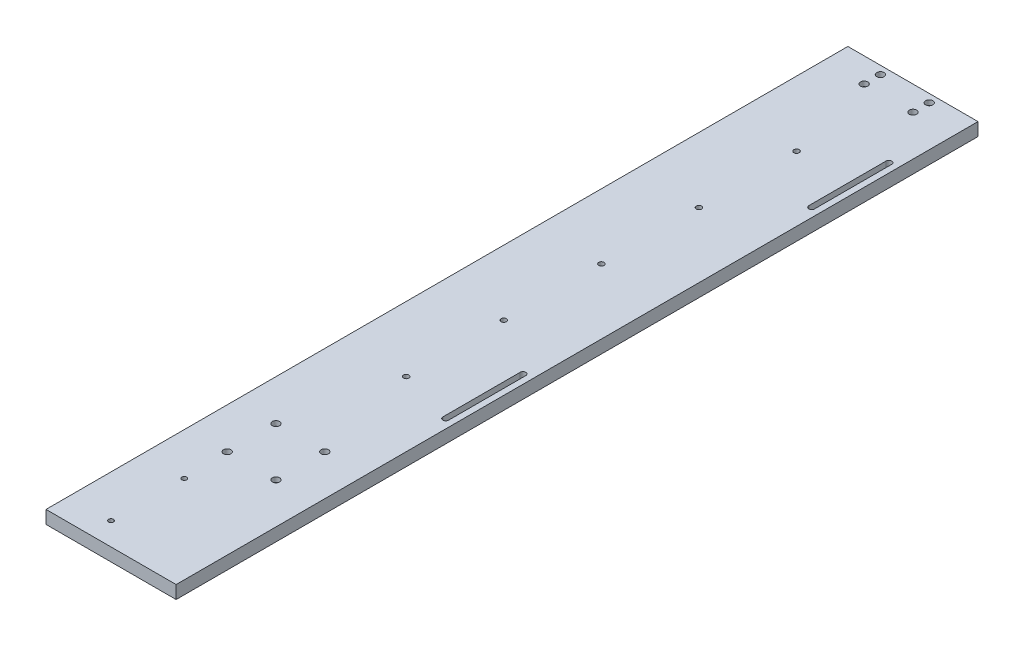
SolidWorks part; units mm, degrees
material "6061 Сплав"
ref_plane "Front" through (0, 0, 0) normal (0, 0, 1) x (1, 0, 0)
ref_plane "Top" through (0, 0, 0) normal (0, 1, 0) x (1, 0, 0)
ref_plane "Right" through (0, 0, 0) normal (1, 0, 0) x (0, 0, -1)
sketch "Эскиз1" plane through (0, 0, 0) normal (0, 0, 1) x (1, 0, 0)
  line L1 (-40, 4) -> (40, 4)
  line L2 (-40, 4) -> (-40, -4)
  line L3 (-40, -4) -> (40, -4)
  line L4 (40, 4) -> (40, -4)
  line L5 (-40, 4) -> (40, -4) construction
  line L6 (-40, -4) -> (40, 4) construction
  point P0 (0, 0)
  dimension "D1" = 80
  dimension "D2" = 8
extrude "Бобышка-Вытянуть1" add sketch "Эскиз1" along normal blind 1000
sketch "Эскиз3" plane through (0, -4, 0) normal (0, -1, 0) x (1, 0, 0)
  line L0 (-40, 1000) -> (-40, 0) construction
  line L1 (-40, 0) -> (40, 0) construction
  circle A0 centre (15, 512) radius 4
  circle A1 centre (-15, 512) radius 4
  dimension "D1" = 30
  dimension "D2" = 25
  dimension "D3" = 512
extrude "Вырез-Вытянуть1" cut sketch "Эскиз3" against normal blind 5
sketch "Эскиз4" plane through (0, 1, 0) normal (0, -1, 0) x (1, 0, 0)
  circle A0 centre (-15, 512) radius 2.25
  circle A1 centre (15, 512) radius 2.25
extrude "Вырез-Вытянуть2" cut sketch "Эскиз4" against normal blind 5
sketch "Эскиз5" plane through (0, -4, 0) normal (0, -1, 0) x (1, 0, 0)
  line L0 (-40, 1000) -> (40, 1000) construction
  line L1 (-40, 1000) -> (-40, 0) construction
  circle A0 centre (-15, 913.6) radius 2.25
  dimension "D1" = 86.4
  dimension "D2" = 25
extrude "Вырез-Вытянуть3" cut sketch "Эскиз5" against normal blind 8
pattern_linear "Линейный массив1" count 2 spacing 30 along (1, 0, 0) count 2 spacing 30 along (0, 0, -1) of "Вырез-Вытянуть3"
sketch "Эскиз6" plane through (0, -4, 0) normal (0, -1, 0) x (1, 0, 0)
  circle A0 centre (-15, 913.6) radius 4
extrude "Вырез-Вытянуть4" cut sketch "Эскиз6" against normal blind 5
pattern_linear "Линейный массив2" count 2 spacing 30 along (1, 0, 0) count 2 spacing 30 along (0, 0, -1) of "Вырез-Вытянуть4"
pattern_linear "Линейный массив11" count 2 spacing 10 along (0, 0, 1) of "Вырез-Вытянуть1", "Вырез-Вытянуть2"
sketch "Эскиз11" plane through (0, -4, 0) normal (0, -1, 0) x (1, 0, 0)
  line L0 (37.5, 220) -> (37.5, 170)
  line L1 (31.5, 170) -> (31.5, 220)
  line L2 (40, 1000) -> (40, 0) construction
  line L3 (-40, 0) -> (40, 0) construction
  arc A0 (31.5, 170) -> (37.5, 170) centre (34.5, 170) ccw
  arc A1 (37.5, 220) -> (31.5, 220) centre (34.5, 220) ccw
  dimension "D1" = 6
  dimension "D2" = 50
  dimension "D3" = 2.5
  dimension "D4" = 170
extrude "Вырез-Вытянуть8" cut sketch "Эскиз11" against normal blind 4
sketch "Эскиз12" plane through (0, 0, 0) normal (0, -1, 0) x (-1, 0, 0)
  line L0 (-36.25, -218.75) -> (-36.25, -171.25)
  line L1 (-32.75, -171.25) -> (-32.75, -218.75)
  line L2 (-37.5, -170) -> (-37.5, -220) construction
  arc A0 (-32.75, -218.75) -> (-36.25, -218.75) centre (-34.5, -218.75) cw
  arc A1 (-32.75, -171.25) -> (-36.25, -171.25) centre (-34.5, -171.25) ccw
  dimension "D1" = 3.5
  dimension "D2" = 1.25
  dimension "D3" = 47.5
  dimension "D4" = 1.25
extrude "Вырез-Вытянуть9" cut sketch "Эскиз12" against normal blind 5
pattern_linear "Линейный массив5" count 2 spacing 610 along (0, 0, 1) of "Вырез-Вытянуть9", "Вырез-Вытянуть8"
pattern_linear "Линейный массив6" count 2 spacing 225 along (0, 0, 1) of "Вырез-Вытянуть8", "Вырез-Вытянуть9"
pattern_linear "Линейный массив7" count 2 spacing 385 along (0, 0, 1) of "Вырез-Вытянуть9", "Вырез-Вытянуть8"
sketch "Эскиз13" plane through (0, -4, 0) normal (0, -1, 0) x (1, 0, 0)
  line L1 (-40, 0) -> (40, 0) construction
  circle A0 centre (-14, 59) radius 1.5
  circle A1 centre (-14, 14) radius 1.5
  dimension "D1" = 14
  dimension "D2" = 45
extrude "Вырез-Вытянуть10" cut sketch "Эскиз13" against normal blind 8
sketch "Эскиз14" plane through (0, -4, 0) normal (0, -1, 0) x (1, 0, 0)
  circle A0 centre (-14, 59) radius 3
  circle A1 centre (-14, 14) radius 3
extrude "Вырез-Вытянуть11" cut sketch "Эскиз14" against normal blind 4
pattern_linear "Линейный массив8" count 2 spacing 927 along (0, 0, 1) of "Вырез-Вытянуть11", "Вырез-Вытянуть10"
sketch "Эскиз15" plane through (0, -4, 0) normal (0, -1, 0) x (1, 0, 0)
  line L0 (40, 1000) -> (40, 0) construction
  line L1 (40, 1000) -> (-40, 1000) construction
  circle A0 centre (0, 421.45) radius 1.65
  point P4 (0, 1000)
  dimension "D1" = 40
  dimension "D2" = 578.55
extrude "Вырез-Вытянуть12" cut sketch "Эскиз15" against normal blind 10
pattern_linear "Линейный массив9" count 5 spacing 60 along (0, 0, -1) of "Вырез-Вытянуть12"
sketch "Эскиз16" plane through (0, -4, 0) normal (0, -1, 0) x (1, 0, 0)
  line L0 (40, 1000) -> (40, 0) construction
  circle A0 centre (0, 578.55) radius 1.65
  dimension "D1" = 40
  dimension "D2" = 578.55
extrude "Вырез-Вытянуть13" cut sketch "Эскиз16" against normal blind 10
pattern_linear "Линейный массив10" count 5 spacing 60 along (0, 0, 1) of "Вырез-Вытянуть13"
sketch "Эскиз17" plane through (0, -4, 0) normal (0, -1, 0) x (1, 0, 0)
  line L0 (-40, 1000) -> (-40, 0) construction
  line L1 (40, 0) -> (-40, 0)
  line L2 (40, 0) -> (40, 507)
  line L3 (40, 507) -> (-40, 507)
  line L4 (-40, 0) -> (-40, 507)
  dimension "D1" = 507
extrude "Вырез-Вытянуть14" cut sketch "Эскиз17" against normal blind 10
